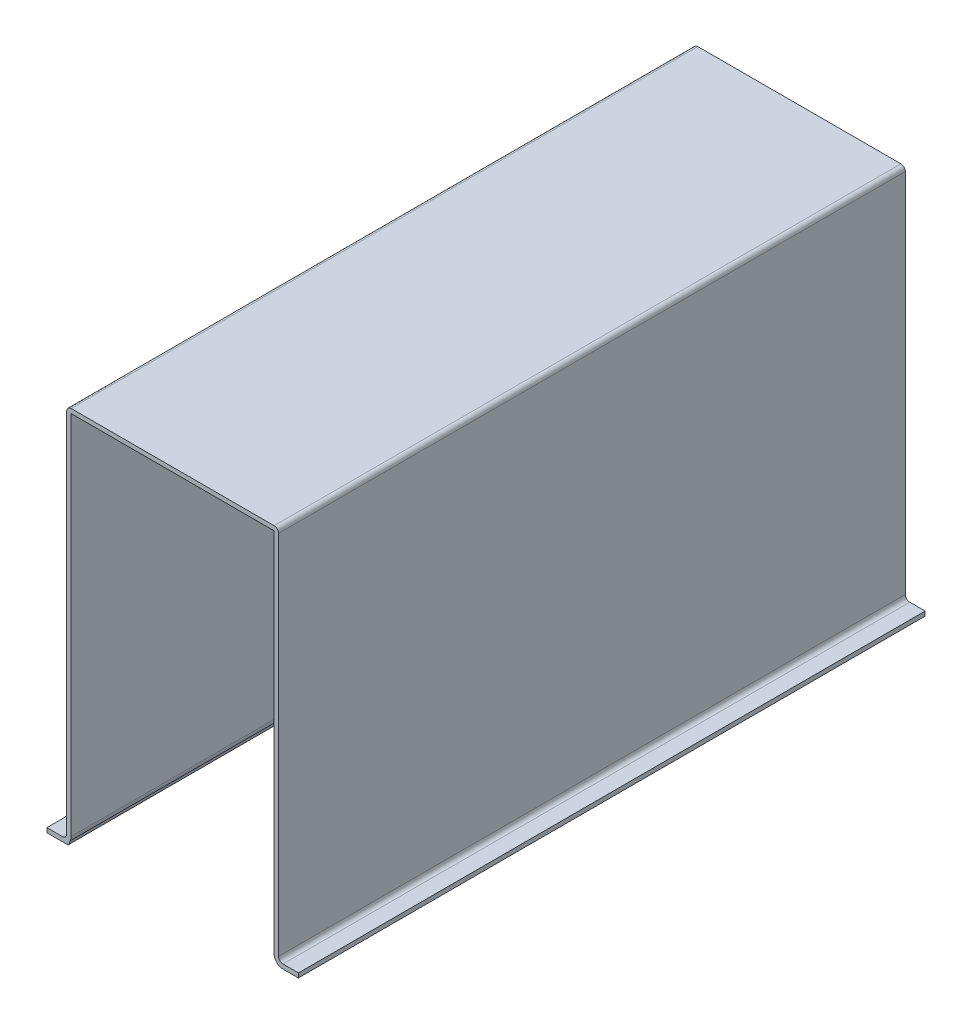
SolidWorks part; units mm, degrees
ref_plane "Front Plane" through (0, 0, 0) normal (0, 0, 1) x (1, 0, 0)
ref_plane "Top Plane" through (0, 0, 0) normal (0, 1, 0) x (1, 0, 0)
ref_plane "Right Plane" through (0, 0, 0) normal (1, 0, 0) x (0, 0, -1)
sketch "Sketch1" plane through (0, 0, 0) normal (0, 0, 1) x (1, 0, 0)
  line L0 (50, 1) -> (52, 1)
  line L1 (-52, 1) -> (-50, 1)
  line L2 (-52, 1) -> (-52, -1)
  line L3 (-52, -1) -> (52, -1)
  line L4 (52, 1) -> (52, -1)
  line L5 (-52, 1) -> (52, -1) construction
  line L6 (-52, -1) -> (52, 1) construction
  line L7 (-48, 3) -> (-48, 169)
  line L8 (48, 3) -> (48, 169)
  line L9 (-46, 171) -> (46, 171)
  arc A0 (-48, 169) -> (-46, 171) centre (-46, 169) cw
  arc A1 (48, 169) -> (46, 171) centre (46, 169) ccw
  arc A2 (-50, 1) -> (-48, 3) centre (-50, 3) ccw
  arc A3 (50, 1) -> (48, 3) centre (50, 3) cw
  point P0 (0, 0)
  point P14 (48, 171)
  point P19 (48, 1)
  dimension "D6" = 2
  dimension "D1" = 2
  dimension "D2" = 104
  dimension "D3" = 96
  dimension "D4" = 4
  dimension "D5" = 170
extrude "Boss-Extrude1" add sketch "Sketch1" along normal blind 284
sketch "Sketch2" plane through (0, 0, 0) normal (0, 0, -1) x (-1, 0, 0)
  line L16 (-46.5359, 1) -> (46.5359, 1)
  line L17 (46, 3) -> (46, 169)
  line L18 (46, 169) -> (-46, 169)
  line L19 (-46, 169) -> (-46, 3)
  line L20 (-46.5359, 1) -> (46.5359, 1)
  line L21 (46, 3) -> (46, 169)
  line L22 (46, 169) -> (-46, 169)
  line L23 (-46, 169) -> (-46, 3)
  arc A8 (46, 3) -> (46.5359, 1) centre (50, 3) ccw
  arc A9 (-46.5359, 1) -> (-46, 3) centre (-50, 3) ccw
  arc A10 (46, 3) -> (46.5359, 1) centre (50, 3) ccw
  arc A11 (-46.5359, 1) -> (-46, 3) centre (-50, 3) ccw
  dimension "D1" = 2
extrude "Cut-Extrude1" cut sketch "Sketch2" against normal through all
sketch "Sketch3" plane through (0, 0, 0) normal (0, 0, -1) x (-1, 0, 0)
  line L1 (-50.0181, -1.0317) -> (49.4614, -2.3281)
  line L2 (-46.5359, 1) -> (46.5359, 1)
  arc A0 (-50.0181, -1.0317) -> (-46.5359, 1) centre (-50.0181, 2.9683) ccw
  arc A1 (46.5359, 1) -> (49.4614, -2.3281) centre (50.5, 1.5347) ccw
  dimension "D1" = 8
  dimension "D2" = 8
extrude "Cut-Extrude3" cut sketch "Sketch3" against normal blind 284
ref_plane "Plane1" through (-52, -1, 0) normal (0, 0, -1) x (-1, 0, 0)
sketch "Sketch5" plane through (-52, 0, 0) normal (-1, 0, 0) x (0, 0, 1)
  line L8 (0, 1) -> (0, -1)
  line L9 (0, -1) -> (284, -1)
  line L10 (284, -1) -> (284, 1)
  line L11 (284, 1) -> (0, 1)
  line L12 (0, 1) -> (0, -1)
  line L13 (0, -1) -> (284, -1)
  line L14 (284, -1) -> (284, 1)
  line L15 (284, 1) -> (0, 1)
  dimension "D1" = 0
extrude "Boss-Extrude2" add sketch "Sketch5" along normal blind 5
sketch "Sketch6" plane through (52, 0, 0) normal (1, 0, 0) x (0, 0, -1)
  line L8 (0, -1) -> (0, 1)
  line L9 (0, 1) -> (-284, 1)
  line L10 (-284, 1) -> (-284, -1)
  line L11 (-284, -1) -> (0, -1)
  line L12 (0, -1) -> (0, 1)
  line L13 (0, 1) -> (-284, 1)
  line L14 (-284, 1) -> (-284, -1)
  line L15 (-284, -1) -> (0, -1)
  dimension "D1" = 0
extrude "Boss-Extrude3" add sketch "Sketch6" along normal blind 5
